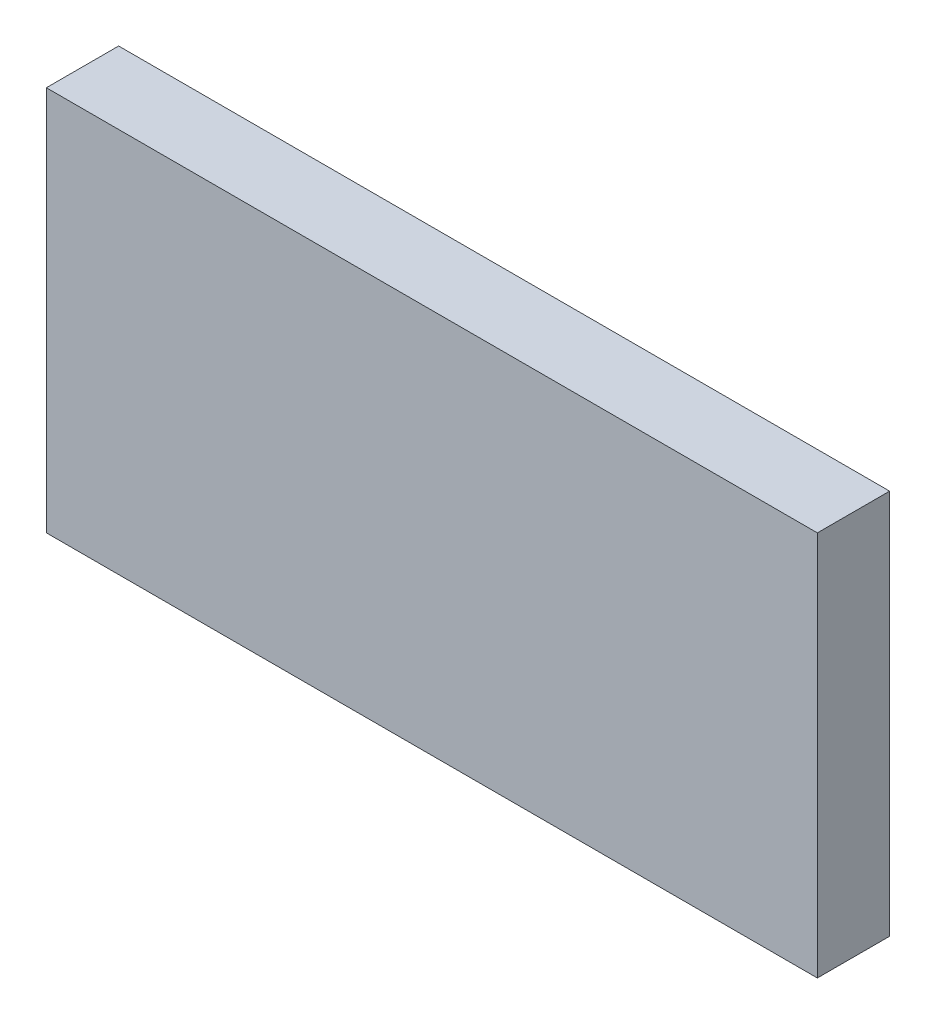
SolidWorks part; units mm, degrees
ref_plane "Front" through (0, 0, 0) normal (0, 0, 1) x (1, 0, 0)
ref_plane "Top" through (0, 0, 0) normal (0, 1, 0) x (1, 0, 0)
ref_plane "Right" through (0, 0, 0) normal (1, 0, 0) x (0, 0, -1)
sketch "Sketch1" plane through (0, 0, 0) normal (0, 0, 1) x (1, 0, 0)
  line L1 (-80, -40) -> (80, -40)
  line L2 (-80, -40) -> (-80, 40)
  line L3 (-80, 40) -> (80, 40)
  line L4 (80, -40) -> (80, 40)
  line L5 (-80, -40) -> (80, 40) construction
  line L6 (-80, 40) -> (80, -40) construction
  point P0 (0, 0)
  dimension "D1" = 80
  dimension "D2" = 160
extrude "Boss-Extrude1" add sketch "Sketch1" along normal blind 15
equation "\"D2@Sketch1\"=\"D1@Sketch1\"*2"
equation "\"h\" = 15"
equation "\"D1@Boss-Extrude1\"= \"h\""
